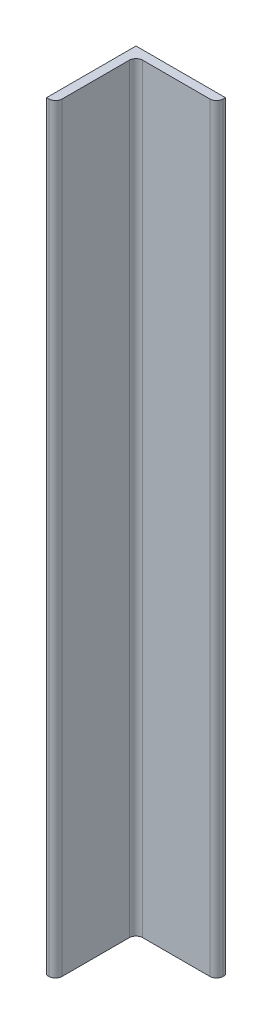
SolidWorks part; units mm, degrees
material "ASTM A36 Steel"
ref_plane "Front Plane" through (0, 0, 0) normal (0, 0, 1) x (1, 0, 0)
ref_plane "Top Plane" through (0, 0, 0) normal (0, 1, 0) x (1, 0, 0)
ref_plane "Right Plane" through (0, 0, 0) normal (1, 0, 0) x (0, 0, -1)
sketch "Sketch1" plane through (0, 0, 0) normal (0, 1, 0) x (1, 0, 0)
  line L0 (-27.4999, 29.2132) -> (-67.4999, 29.2132)
  line L1 (-67.4999, 29.2132) -> (-67.4999, -10.7868)
  line L2 (-67.4999, -10.7868) -> (-66.4999, -10.7868)
  line L3 (-63.4999, -7.7868) -> (-63.4999, 22.2132)
  line L4 (-60.4999, 25.2132) -> (-30.4999, 25.2132)
  line L5 (-27.4999, 28.2132) -> (-27.4999, 29.2132)
  arc A0 (-66.4999, -10.7868) -> (-63.4999, -7.7868) centre (-66.4999, -7.7868) ccw
  arc A1 (-63.4999, 22.2132) -> (-60.4999, 25.2132) centre (-60.4999, 22.2132) cw
  arc A2 (-30.4999, 25.2132) -> (-27.4999, 28.2132) centre (-30.4999, 28.2132) ccw
  point P8 (-63.4999, -10.7868)
  point P13 (-27.4999, 25.2132)
  dimension "D5" = 3
  dimension "D1" = 40
  dimension "D2" = 40
  dimension "D3" = 4
  dimension "D4" = 4
extrude "Boss-Extrude1" add sketch "Sketch1" along normal blind 340
